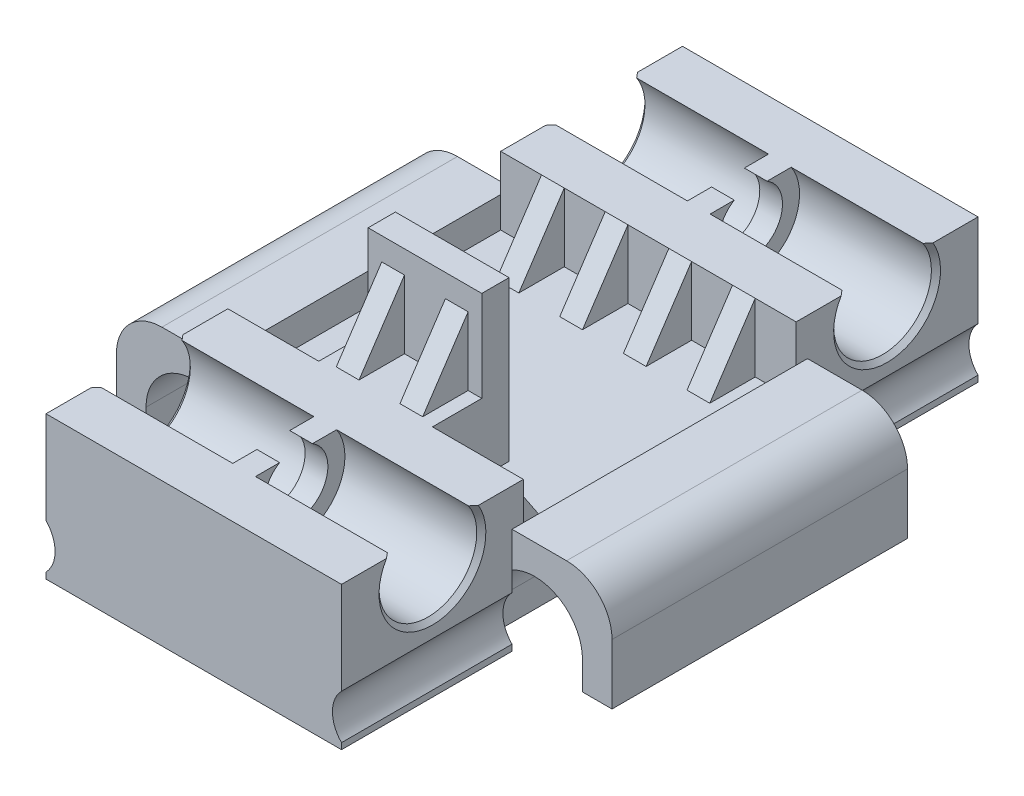
SolidWorks part; units mm, degrees
material "三聚氰胺甲醛树脂"
ref_plane "前视基准面" through (0, 0, 0) normal (0, 0, 1) x (1, 0, 0)
ref_plane "上视基准面" through (0, 0, 0) normal (0, 1, 0) x (1, 0, 0)
ref_plane "右视基准面" through (0, 0, 0) normal (1, 0, 0) x (0, 0, -1)
sketch "草图1" plane through (0, 0, 0) normal (0, 1, 0) x (1, 0, 0)
  line L1 (-32.5, 70) -> (32.5, 70)
  line L2 (-32.5, 70) -> (-32.5, -70)
  line L3 (-32.5, -70) -> (32.5, -70)
  line L4 (32.5, 70) -> (32.5, -70)
  line L5 (-32.5, 70) -> (32.5, -70) construction
  line L6 (-32.5, -70) -> (32.5, 70) construction
  point P0 (0, 0)
  dimension "D1" = 65
  dimension "D2" = 140
extrude "凸台-拉伸1" add sketch "草图1" along normal blind 31.5 contours L1 L4 L3 L2
sketch "草图2" plane through (-32.5, 0, 0) normal (-1, 0, 0) x (0, 0, 1)
  line L0 (-70, 0) -> (70, 0) construction
  line L1 (0, 37.2602) -> (0, -22.1353) construction
  circle A0 centre (-50, 25.5) radius 10.75
  circle A1 centre (50, 25.5) radius 10.75
  dimension "D1" = 21.5
  dimension "D2" = 21.5
  dimension "D3" = 25.5
  dimension "D4" = 25.5
  dimension "D5" = 50
  dimension "D6" = 50
extrude "切除-拉伸1" cut sketch "草图2" against normal blind 30 contours A0 | A1
sketch "草图3" plane through (32.5, 0, 0) normal (1, 0, 0) x (0, 0, -1)
  line L0 (70, 0) -> (-70, 0) construction
  line L1 (0, 42.9776) -> (0, -30.1843) construction
  circle A0 centre (-50, 25.5) radius 10.75
  circle A1 centre (50, 25.5) radius 10.75
  dimension "D1" = 21.5
  dimension "D2" = 21.5
  dimension "D3" = 25.5
  dimension "D4" = 25.5
  dimension "D5" = 50
  dimension "D6" = 50
extrude "切除-拉伸2" cut sketch "草图3" against normal blind 30
chamfer "倒角1" distance 1 angle 45 1 edges at (32.5, 14.75, 50)
chamfer "倒角2" distance 1 angle 45 3 edges at (-32.5, 14.75, 50) (-32.5, 14.75, -50) (32.5, 14.75, -50)
sketch "草图4" plane through (0, 31.5, 0) normal (0, 1, 0) x (1, 0, 0)
  line L0 (-68.5304, 0) -> (104.2383, 0) construction
  line L2 (-12.5, -13.15) -> (12.5, -13.15)
  line L3 (-12.5, -13.15) -> (-12.5, -19.15)
  line L4 (-12.5, -19.15) -> (12.5, -19.15)
  line L5 (12.5, -13.15) -> (12.5, -19.15)
  dimension "D1" = 13.15
  dimension "D2" = 6
  dimension "D3" = 25
  dimension "D4" = 12.5
extrude "凸台-拉伸2" add sketch "草图4" along normal blind 20 contours L4 L5 L2 L3
ref_plane "基准面3" through (7, 0, 0) normal (1, 0, 0) x (0, 0, -1)
ref_plane "基准面4" through (-7, 0, 0) normal (1, 0, 0) x (0, 0, -1)
sketch "草图7" plane through (7, 0, 0) normal (1, 0, 0) x (0, 0, -1)
  line L0 (-19.15, 46.5) -> (-19.15, 31.5)
  line L1 (-19.15, 51.5) -> (-19.15, 31.5) construction
  line L2 (-19.15, 31.5) -> (-29.15, 31.5)
  line L3 (39.8974, 31.5) -> (-39.8974, 31.5) construction
  line L4 (-29.15, 31.5) -> (-19.15, 46.5)
  dimension "D1" = 15
  dimension "D2" = 10
sketch "草图8" plane through (-7, 0, 0) normal (1, 0, 0) x (0, 0, -1)
  line L0 (-19.15, 46.5) -> (-19.15, 31.5)
  line L1 (-19.15, 31.5) -> (-29.15, 31.5)
  line L2 (-29.15, 31.5) -> (-19.15, 46.5)
extrude "凸台-拉伸4" add sketch "草图7" along normal mid plane 5
extrude "凸台-拉伸5" add sketch "草图8" along normal mid plane 5
sketch "草图9" plane through (0, 31.5, 0) normal (0, 1, 0) x (1, 0, 0)
  line L0 (-32.5, 39.8974) -> (-32.5, -39.8974) construction
  line L1 (-32.5, 30.0002) -> (32.5, 30.0002)
  line L2 (-32.5, 30.0002) -> (-32.5, -13.15)
  line L3 (-12.5, -13.15) -> (12.5, -13.15)
  line L4 (32.5, 30.0002) -> (32.5, -13.15)
  line L5 (32.5, 39.8974) -> (32.5, -39.8974) construction
  line L8 (-32.5, -13.15) -> (-32.5, -30.0002)
  line L9 (-32.5, -30.0002) -> (-12.5, -30.0002)
  line L10 (-12.5, -13.15) -> (-12.5, -30.0002)
  line L12 (12.5, -13.15) -> (12.5, -30.0002)
  line L13 (12.5, -30.0002) -> (32.5, -30.0002)
  line L14 (32.5, -13.15) -> (32.5, -30.0002)
  line L19 (-31.5, 41.0802) -> (-2.5, 41.0802) construction
  line L20 (-2.5, -41.0802) -> (-31.5, -41.0802) construction
  line L21 (31.5, -41.0802) -> (2.5, -41.0802) construction
  line L22 (0, 73.3005) -> (0, -82.0291) construction
  dimension "D1" = 11.08
  dimension "D2" = 11.08
  dimension "D3" = 11.08
  dimension "D4" = 12.5
extrude "切除-拉伸3" cut sketch "草图9" against normal blind 15
ref_plane "基准面5" through (21, 0, 0) normal (1, 0, 0) x (0, 0, -1)
ref_plane "基准面6" through (-21, 0, 0) normal (1, 0, 0) x (0, 0, -1)
sketch "草图11" plane through (7, 0, 0) normal (1, 0, 0) x (0, 0, -1)
  line L0 (30.0002, 31.5) -> (30.0002, 16.5)
  line L1 (30.0002, 16.5) -> (20.0002, 16.5)
  line L2 (30.0002, 16.5) -> (-30.0002, 16.5) construction
  line L3 (20.0002, 16.5) -> (30.0002, 31.5)
  dimension "D1" = 10
sketch "草图12" plane through (-7, 0, 0) normal (1, 0, 0) x (0, 0, -1)
  line L0 (30.0002, 31.5) -> (30.0002, 16.5)
  line L1 (30.0002, 16.5) -> (20.0002, 16.5)
  line L2 (20.0002, 16.5) -> (30.0002, 31.5)
sketch "草图13" plane through (21, 0, 0) normal (1, 0, 0) x (0, 0, -1)
  line L0 (30.0002, 31.5) -> (30.0002, 16.5)
  line L1 (30.0002, 16.5) -> (20.0002, 16.5)
  line L2 (20.0002, 16.5) -> (30.0002, 31.5)
sketch "草图14" plane through (-21, 0, 0) normal (1, 0, 0) x (0, 0, -1)
  line L0 (30.0002, 31.5) -> (30.0002, 16.5)
  line L1 (30.0002, 16.5) -> (20.0002, 16.5)
  line L2 (20.0002, 16.5) -> (30.0002, 31.5)
extrude "凸台-拉伸6" add sketch "草图11" along normal mid plane 5
extrude "凸台-拉伸7" add sketch "草图13" along normal mid plane 5 contours L2 L0 L1
extrude "凸台-拉伸8" add sketch "草图12" along normal mid plane 5 contours L2 L0 L1
extrude "凸台-拉伸9" add sketch "草图14" along normal mid plane 5 contours L2 L0 L1
sketch "草图15" plane through (-21, 0, 0) normal (1, 0, 0) x (0, 0, -1)
  line L0 (-30.0002, 31.5) -> (-30.0002, 16.5)
  line L2 (-30.0002, 16.5) -> (-20.0002, 16.5)
  line L4 (-20.0002, 16.5) -> (-30.0002, 31.5)
  dimension "D1" = 10
  dimension "D2" = 15
sketch "草图16" plane through (21, 0, 0) normal (1, 0, 0) x (0, 0, -1)
  line L0 (-30.0002, 31.5) -> (-30.0002, 16.5)
  line L1 (-30.0002, 16.5) -> (-20.0002, 16.5)
  line L2 (-20.0002, 16.5) -> (-30.0002, 31.5)
extrude "凸台-拉伸10" add sketch "草图15" against normal blind 5
extrude "凸台-拉伸11" add sketch "草图16" along normal blind 5
sketch "草图17" plane through (32.5, 0, 0) normal (1, 0, 0) x (0, 0, -1)
  line L0 (-80.6314, 19.25) -> (89.2158, 19.25) construction
  arc A0 (-58.9198, 31.5) -> (-41.0802, 31.5) centre (-50, 25.5) ccw construction
  point P5 (-50, 14.75)
  dimension "D1" = 4.5
sketch "草图18" plane through (-2.5, 0, 0) normal (-1, 0, 0) x (0, 0, 1)
  circle A0 centre (50, 25.5) radius 7
  circle A1 centre (-50, 25.5) radius 7
  dimension "D1" = 14
  dimension "D2" = 14
extrude "切除-拉伸7" cut sketch "草图18" against normal through all contours A1 | A0
sketch "草图19" plane through (32.5, 0, 0) normal (1, 0, 0) x (0, 0, -1)
  line L0 (-80.6314, 19.25) -> (89.2158, 19.25) construction
  line L1 (-32.5002, 0) -> (32.5002, 0)
  line L2 (-32.5002, 0) -> (-32.5002, 23.25)
  line L3 (-32.5002, 23.25) -> (32.5002, 23.25)
  line L4 (32.5002, 0) -> (32.5002, 23.25)
  line L5 (-30.0002, 31.5) -> (-30.0002, 16.5) construction
  line L6 (30.0002, 31.5) -> (30.0002, 16.5) construction
  dimension "D1" = 4
  dimension "D2" = 23.25
  dimension "D3" = 2.5
  dimension "D4" = 2.5
sketch "草图20" plane through (-32.5, 0, 0) normal (-1, 0, 0) x (0, 0, 1)
  line L1 (-32.5002, 23.25) -> (32.5002, 23.25)
  line L2 (-32.5002, 23.25) -> (-32.5002, 0)
  line L3 (-32.5002, 0) -> (32.5002, 0)
  line L4 (32.5002, 23.25) -> (32.5002, 0)
extrude "凸台-拉伸12" add sketch "草图19" along normal blind 22 contours L3 L4 L1 L2
extrude "凸台-拉伸13" add sketch "草图20" along normal blind 22 contours L1 L4 L3 L2
sketch "草图21" plane through (0, 0, 32.5002) normal (0, 0, 1) x (1, 0, 0)
  line L0 (-54.5, 0) -> (-32.5, 0) construction
  line L1 (54.5, 0) -> (32.5, 0) construction
  line L2 (0, 58.9377) -> (0, -16.5256) construction
  line L4 (-32.5, 31.5) -> (-32.5, 0) construction
  line L5 (32.5, 31.5) -> (32.5, 0) construction
  line L6 (-48, 6.25) -> (-48, 0)
  line L7 (-48, 0) -> (-27, 0)
  line L8 (-32.5, 0) -> (32.5, 0) construction
  line L9 (-27, 0) -> (-27, 6.25)
  line L10 (27, 6.25) -> (27, 0)
  line L11 (27, 0) -> (48, 0)
  line L12 (48, 0) -> (48, 6.25)
  arc A0 (48, 6.25) -> (27, 6.25) centre (37.5, 6.25) ccw
  arc A1 (-27, 6.25) -> (-48, 6.25) centre (-37.5, 6.25) ccw
  dimension "D1" = 21
  dimension "D2" = 21
  dimension "D3" = 6.25
  dimension "D4" = 6.25
  dimension "D5" = 5
  dimension "D6" = 5
extrude "切除-拉伸8" cut sketch "草图21" against normal blind 30 contours A1 L6 L7 L9 | A0 L10 L11 L12
sketch "草图22" plane through (0, 0, 70) normal (0, 0, 1) x (1, 0, 0)
  circle A0 centre (-37.5, 6.25) radius 7
  circle A1 centre (37.5, 6.25) radius 7
  dimension "D1" = 14
  dimension "D2" = 14
extrude "切除-拉伸9" cut sketch "草图22" against normal through all contours A1 | A0
sketch "草图23" plane through (0, 0, -32.5002) normal (0, 0, -1) x (-1, 0, 0)
  line L0 (-48, 6.25) -> (-48, 0)
  line L1 (-48, 0) -> (-27, 0)
  line L2 (-27, 0) -> (-27, 6.25)
  line L3 (48, 6.25) -> (48, 0)
  line L4 (48, 0) -> (27, 0)
  line L5 (32.5, 0) -> (-32.5, 0) construction
  line L6 (27, 0) -> (27, 6.25)
  arc A0 (-27, 6.25) -> (-48, 6.25) centre (-37.5, 6.25) ccw
  arc A1 (48, 6.25) -> (27, 6.25) centre (37.5, 6.25) ccw
  dimension "D1" = 21
  dimension "D2" = 21
extrude "切除-拉伸10" cut sketch "草图23" against normal blind 30
fillet "圆角7" radius 10 2 edges at (-54.5, 23.25, 0) (54.5, 23.25, 0)
